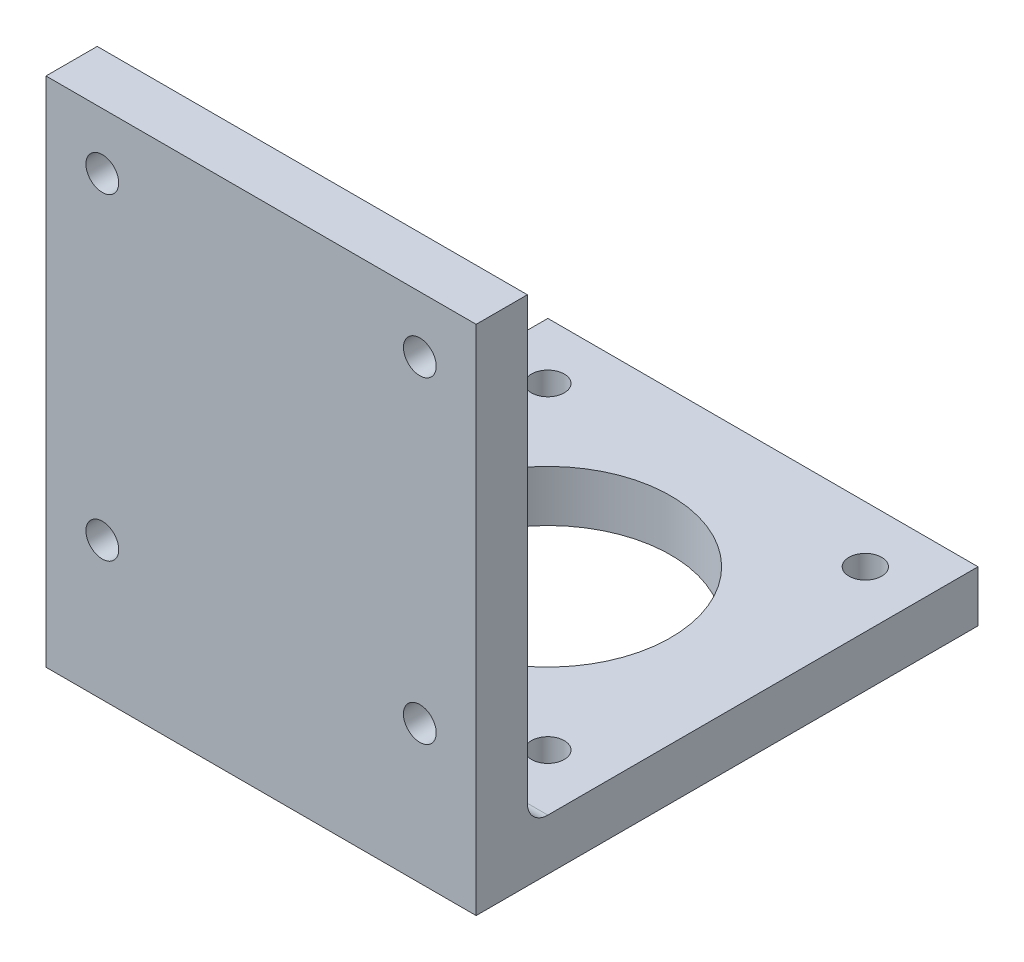
SolidWorks part; units mm, degrees
ref_plane "前视基准面" through (0, 0, 0) normal (0, 0, 1) x (1, 0, 0)
ref_plane "上视基准面" through (0, 0, 0) normal (0, 1, 0) x (1, 0, 0)
ref_plane "右视基准面" through (0, 0, 0) normal (1, 0, 0) x (0, 0, -1)
sketch "草图1" plane through (0, 0, 0) normal (0, 1, 0) x (1, 0, 0)
  line L1 (-21, -21) -> (21, -21) construction
  line L2 (-21, -21) -> (-21, 21)
  line L3 (-21, 21) -> (21, 21)
  line L4 (21, -21) -> (21, 21)
  line L5 (-21, -21) -> (21, 21) construction
  line L6 (-21, 21) -> (21, -21) construction
  line L7 (-15.5, -15.5) -> (15.5, -15.5) construction
  line L8 (-15.5, -15.5) -> (-15.5, 15.5) construction
  line L9 (-15.5, 15.5) -> (15.5, 15.5) construction
  line L10 (15.5, -15.5) -> (15.5, 15.5) construction
  line L11 (-15.5, -15.5) -> (15.5, 15.5) construction
  line L12 (-15.5, 15.5) -> (15.5, -15.5) construction
  line L13 (-21, -21) -> (21, -21) construction
  line L14 (-21, -21) -> (-21, -23)
  line L15 (-21, -23) -> (21, -23)
  line L16 (21, -21) -> (21, -23)
  circle A0 centre (-15.5, 15.5) radius 1.6
  circle A1 centre (15.5, 15.5) radius 1.6
  circle A2 centre (-15.5, -15.5) radius 1.6
  circle A3 centre (15.5, -15.5) radius 1.6
  circle A4 centre (0, 0) radius 12
  point P0 (0, 0)
  point P12 (0, 0)
  dimension "D3" = 3.2
  dimension "D4" = 3.2
  dimension "D5" = 3.2
  dimension "D6" = 3.2
  dimension "D9" = 24
  dimension "D1" = 42
  dimension "D2" = 42
  dimension "D7" = 31
  dimension "D8" = 2
extrude "凸台-拉伸1" add sketch "草图1" along normal blind 5
sketch "草图4" plane through (0, 0, 23) normal (0, 0, 1) x (1, 0, 0)
  line L0 (-21, 8) -> (21, 8) construction
  line L1 (-21, 0) -> (21, 0)
  line L2 (-21, 0) -> (-21, 50)
  line L3 (-21, 50) -> (21, 50)
  line L4 (21, 0) -> (21, 50)
  line L5 (21, 8) -> (-21, 50) construction
  line L6 (-21, 8) -> (21, 50) construction
  line L7 (21, 5) -> (21, 0) construction
  line L8 (-15.5, 13.5) -> (15.5, 13.5) construction
  line L9 (-15.5, 13.5) -> (-15.5, 44.5) construction
  line L10 (-15.5, 44.5) -> (15.5, 44.5) construction
  line L11 (15.5, 13.5) -> (15.5, 44.5) construction
  line L12 (-15.5, 13.5) -> (15.5, 44.5) construction
  line L13 (-15.5, 44.5) -> (15.5, 13.5) construction
  circle A0 centre (-15.5, 44.5) radius 1.6
  circle A1 centre (15.5, 44.5) radius 1.6
  circle A2 centre (-15.5, 13.5) radius 1.6
  circle A3 centre (15.5, 13.5) radius 1.6
  point P7 (0, 29)
  dimension "D4" = 3.2
  dimension "D5" = 3.2
  dimension "D6" = 3.2
  dimension "D7" = 3.2
  dimension "D1" = 50
  dimension "D2" = 42
  dimension "D3" = 31
extrude "凸台-拉伸4" add sketch "草图4" along normal blind 5
fillet "圆角1" radius 2 1 edges at (0, 5, 23)
